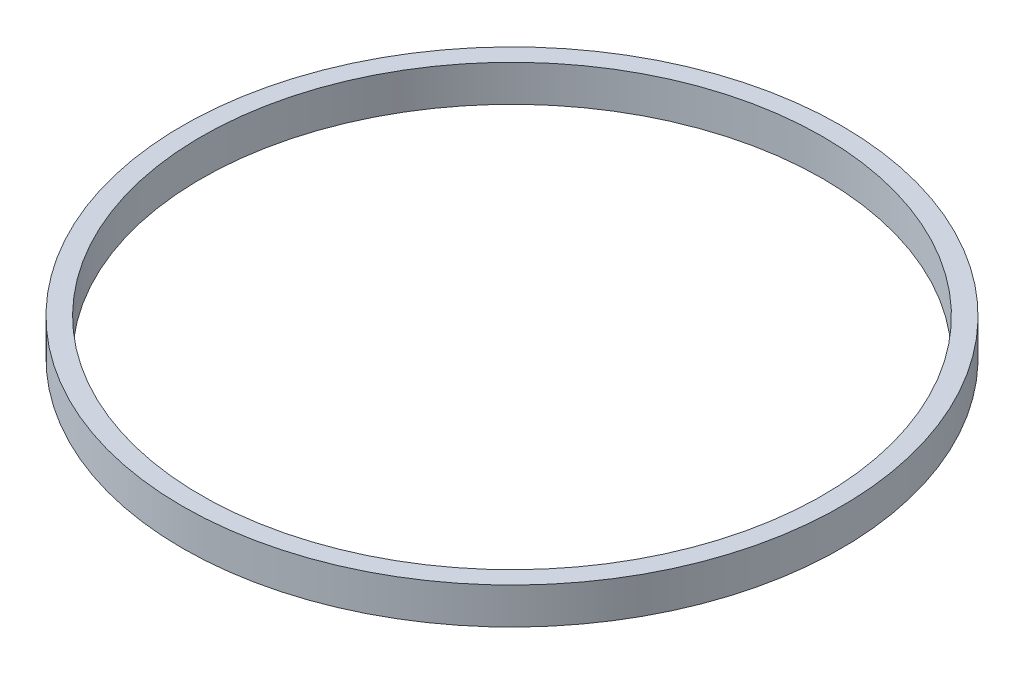
SolidWorks part; units mm, degrees
ref_plane "Front Plane" through (0, 0, 0) normal (0, 0, 1) x (1, 0, 0)
ref_plane "Top Plane" through (0, 0, 0) normal (0, 1, 0) x (1, 0, 0)
ref_plane "Right Plane" through (0, 0, 0) normal (1, 0, 0) x (0, 0, -1)
sketch "Sketch1" plane through (0, 0, 0) normal (0, 0, 1) x (1, 0, 0)
  line L0 (0, 0) -> (0, 6.0593) construction
  line L5 (-22.225, 2.6035) -> (-23.5712, 2.6035)
  line L9 (-22.225, 2.6035) -> (-22.225, 0)
  line L10 (-22.225, 0) -> (-23.5712, 0)
  line L11 (-23.5712, 0) -> (-23.5712, 2.6035)
  dimension "D1" = 22.225
  dimension "D2" = 2.6035
  dimension "D3" = 1.3462
revolve "Revolve1" add sketch "Sketch1" angle 360 about L0
